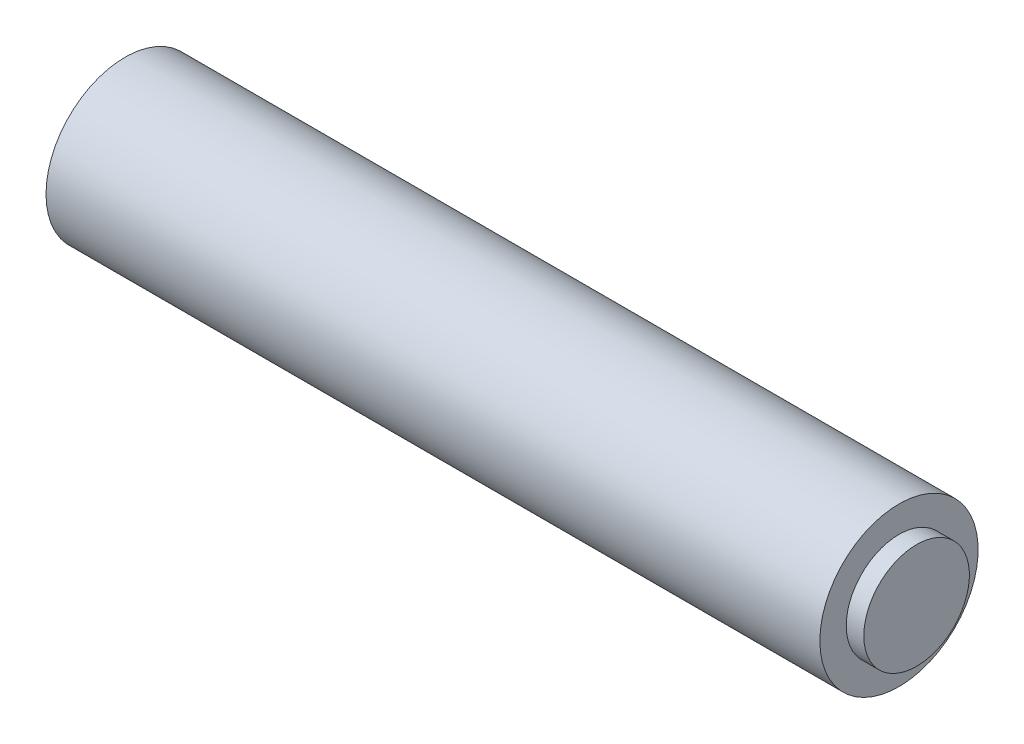
SolidWorks part; units mm, degrees
ref_plane "Piano frontale" through (0, 0, 0) normal (0, 0, 1) x (1, 0, 0)
ref_plane "Piano superiore" through (0, 0, 0) normal (0, 1, 0) x (1, 0, 0)
ref_plane "Piano destro" through (0, 0, 0) normal (1, 0, 0) x (0, 0, -1)
sketch "Schizzo3" plane through (0, 0, 0) normal (0, 0, 1) x (1, 0, 0)
  line L0 (-60.9654, 0) -> (60.1788, 0) construction
  line L1 (-35.5462, 0) -> (-35.5462, 3)
  line L2 (-35.5462, 3) -> (-34.5462, 3)
  line L3 (-34.5462, 3) -> (-34.5462, 4.5)
  line L4 (-34.5462, 4.5) -> (9.4538, 4.5)
  line L5 (9.4538, 4.5) -> (9.4538, 3)
  line L6 (9.4538, 3) -> (10.4538, 3)
  line L7 (10.4538, 3) -> (10.4538, 0)
  line L8 (-35.5462, 0) -> (10.4538, 0)
  dimension "D1" = 1
  dimension "D2" = 1
  dimension "D3" = 44
  dimension "D4" = 4.5
  dimension "D5" = 3
  dimension "D6" = 1.5
  dimension "D7" = 3
revolve "Rivoluzione1" add sketch "Schizzo3" angle 360 about L0
